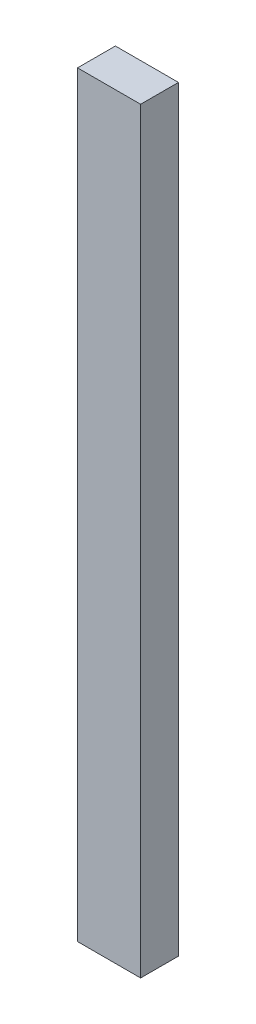
SolidWorks part; units mm, degrees
ref_plane "Plano frontal" through (0, 0, 0) normal (0, 0, 1) x (1, 0, 0)
ref_plane "Plano superior" through (0, 0, 0) normal (0, 1, 0) x (1, 0, 0)
ref_plane "Plano direito" through (0, 0, 0) normal (1, 0, 0) x (0, 0, -1)
sketch "Esboço1" plane through (0, 0, 0) normal (0, 0, 1) x (1, 0, 0)
  line L5 (3.3966, 0) -> (-6.6034, 0)
  line L6 (3.3966, 0) -> (3.3966, 120)
  line L7 (3.3966, 120) -> (-6.6034, 120)
  line L8 (-6.6034, 0) -> (-6.6034, 120)
  dimension "D1" = 10
  dimension "D2" = 120
extrude "Ressalto-extrusão1" add sketch "Esboço1" along normal blind 6
